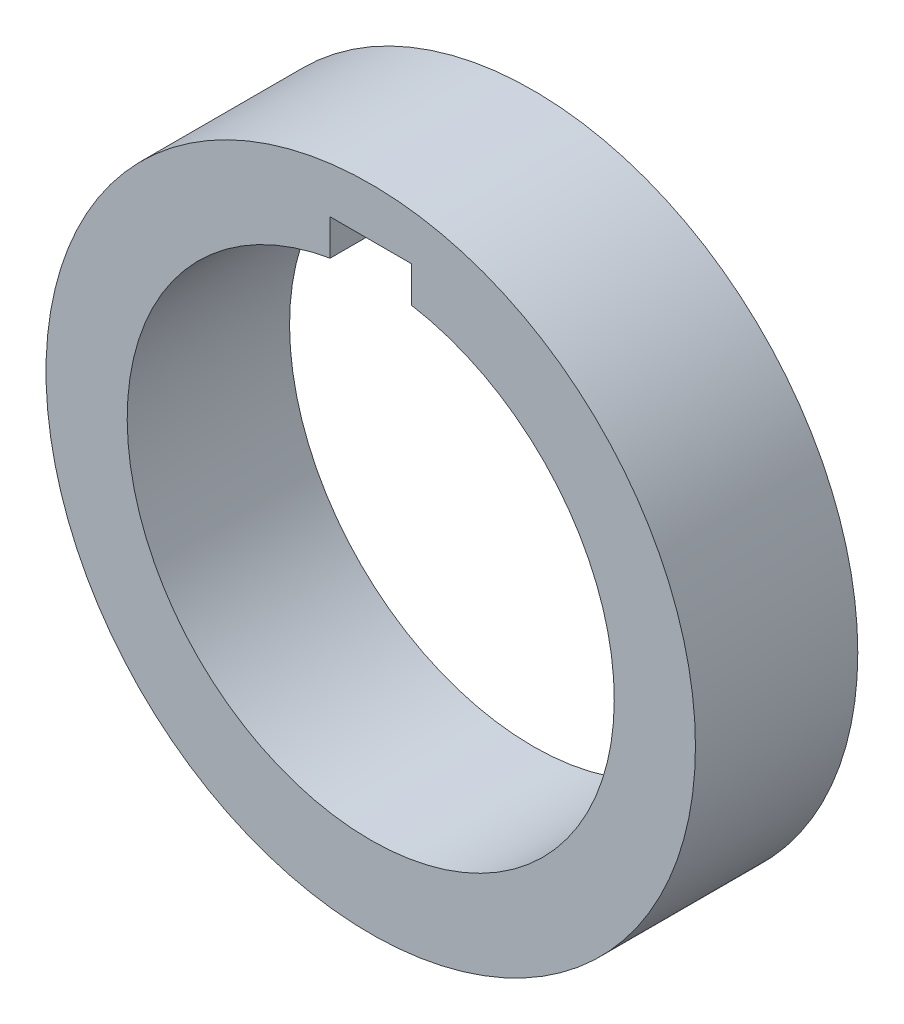
SolidWorks part; units mm, degrees
ref_plane "Front Plane" through (0, 0, 0) normal (0, 0, 1) x (1, 0, 0)
ref_plane "Top Plane" through (0, 0, 0) normal (0, 1, 0) x (1, 0, 0)
ref_plane "Right Plane" through (0, 0, 0) normal (1, 0, 0) x (0, 0, -1)
sketch "Sketch1" plane through (0, 0, 0) normal (0, 0, 1) x (1, 0, 0)
  line L0 (-2.5, 9.6825) -> (-2.5, 11.43)
  line L1 (-2.5, 11.43) -> (2.5, 11.43)
  line L2 (2.5, 11.43) -> (2.5, 9.6825)
  line L3 (-2.5, 14.7902) -> (-2.5, 17)
  line L4 (-2.5, 17) -> (2.5, 17)
  line L5 (2.5, 17) -> (2.5, 14.7902)
  arc A0 (-2.5, 14.7902) -> (2.5, 14.7902) centre (0, 0) ccw
  arc A1 (-2.5, 9.6825) -> (2.5, 9.6825) centre (0, 0) ccw
  circle A2 centre (0, 0) radius 20
  point P10 (0, 17)
  point P13 (0, 11.43)
  dimension "D1" = 20
  dimension "D2" = 30
  dimension "D6" = 40
  dimension "D3" = 5
  dimension "D4" = 11.43
  dimension "D5" = 17
extrude "Boss-Extrude1" add sketch "Sketch1" along normal blind 10 contours A2 | A0 L5 L4 L3
